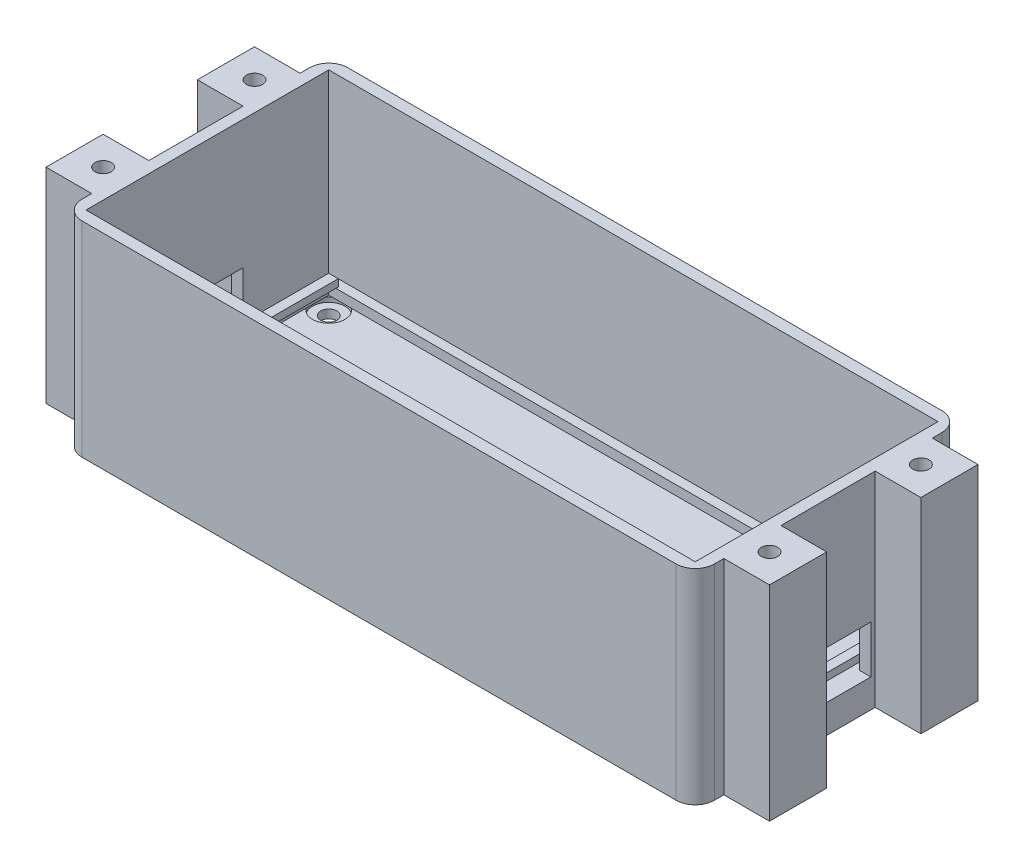
SolidWorks part; units mm, degrees
ref_plane "Front Plane" through (0, 0, 0) normal (0, 0, 1) x (1, 0, 0)
ref_plane "Top Plane" through (0, 0, 0) normal (0, 1, 0) x (1, 0, 0)
ref_plane "Right Plane" through (0, 0, 0) normal (1, 0, 0) x (0, 0, -1)
sketch "Sk_Shell" plane through (0, 0, 0) normal (0, 1, 0) x (1, 0, 0)
  line L0 (4, 0) -> (128.8, 0)
  line L1 (132.8, 4) -> (132.8, 51.8)
  line L2 (128.8, 55.8) -> (4, 55.8)
  line L3 (0, 51.8) -> (0, 4)
  arc A0 (128.8, 0) -> (132.8, 4) centre (128.8, 4) ccw
  arc A1 (132.8, 51.8) -> (128.8, 55.8) centre (128.8, 51.8) ccw
  arc A2 (4, 55.8) -> (0, 51.8) centre (4, 51.8) ccw
  arc A3 (0, 4) -> (4, 0) centre (4, 4) ccw
extrude "Shell" add sketch "Sk_Shell" along normal blind 43
sketch "Sk_Tabs" plane through (0, 0, 0) normal (0, 1, 0) x (1, 0, 0)
  line L1 (-9.6, 6) -> (0, 6)
  line L2 (-9.6, 6) -> (-9.6, 18)
  line L3 (-9.6, 18) -> (0, 18)
  line L4 (0, 6) -> (0, 18)
  line L6 (132.8, 6) -> (142.4, 6)
  line L7 (132.8, 6) -> (132.8, 18)
  line L8 (132.8, 18) -> (142.4, 18)
  line L9 (142.4, 6) -> (142.4, 18)
  line L11 (-9.6, 37.8) -> (0, 37.8)
  line L12 (-9.6, 37.8) -> (-9.6, 49.8)
  line L13 (-9.6, 49.8) -> (0, 49.8)
  line L14 (0, 37.8) -> (0, 49.8)
  line L16 (132.8, 37.8) -> (142.4, 37.8)
  line L17 (132.8, 37.8) -> (132.8, 49.8)
  line L18 (132.8, 49.8) -> (142.4, 49.8)
  line L19 (142.4, 37.8) -> (142.4, 49.8)
extrude "Mounting Tabs" add sketch "Sk_Tabs" along normal blind 43
ref_plane "Plane_FloorTop" through (0, 2.8, 0) normal (0, 1, 0) x (1, 0, 0)
sketch "Sk_Cavity" plane through (0, 2.8, 0) normal (0, 1, 0) x (1, 0, 0)
  line L1 (2.4, 2.4) -> (130.4, 2.4)
  line L2 (2.4, 2.4) -> (2.4, 53.4)
  line L3 (2.4, 53.4) -> (130.4, 53.4)
  line L4 (130.4, 2.4) -> (130.4, 53.4)
extrude "Cavity" cut sketch "Sk_Cavity" along normal through all
ref_plane "Plane_Lip" through (0, 4, 0) normal (0, 1, 0) x (1, 0, 0)
sketch "Sk_Lip" plane through (0, 4, 0) normal (0, 1, 0) x (1, 0, 0)
  line L1 (2.4, 2.4) -> (130.4, 2.4)
  line L2 (2.4, 2.4) -> (2.4, 53.4)
  line L3 (2.4, 53.4) -> (130.4, 53.4)
  line L4 (130.4, 2.4) -> (130.4, 53.4)
  line L6 (4.4, 4.4) -> (128.4, 4.4)
  line L7 (4.4, 4.4) -> (4.4, 51.4)
  line L8 (4.4, 51.4) -> (128.4, 51.4)
  line L9 (128.4, 4.4) -> (128.4, 51.4)
extrude "Board Lip" add sketch "Sk_Lip" along normal blind 2
ref_plane "Plane_LipTop" through (0, 6, 0) normal (0, 1, 0) x (1, 0, 0)
sketch "Sk_Rails" plane through (0, 6, 0) normal (0, 1, 0) x (1, 0, 0)
  line L1 (3.9, 3.9) -> (5.9, 3.9)
  line L2 (3.9, 3.9) -> (3.9, 51.9)
  line L3 (3.9, 51.9) -> (5.9, 51.9)
  line L4 (5.9, 3.9) -> (5.9, 51.9)
  line L6 (126.9, 3.9) -> (128.9, 3.9)
  line L7 (126.9, 3.9) -> (126.9, 51.9)
  line L8 (126.9, 51.9) -> (128.9, 51.9)
  line L9 (128.9, 3.9) -> (128.9, 51.9)
extrude "Board Rails" add sketch "Sk_Rails" along normal blind 1.5
sketch "Sk_SlotA" plane through (0, 0, 0) normal (1, 0, 0) x (0, 0, -1)
  line L1 (20.4, 6) -> (35.4, 6)
  line L2 (20.4, 6) -> (20.4, 16)
  line L3 (20.4, 16) -> (35.4, 16)
  line L4 (35.4, 6) -> (35.4, 16)
extrude "Cable Slot 15x10" cut sketch "Sk_SlotA" along normal blind 3
ref_plane "Plane_EndB" through (132.8, 0, 0) normal (1, 0, 0) x (0, 0, -1)
sketch "Sk_SlotB" plane through (132.8, 0, 0) normal (1, 0, 0) x (0, 0, -1)
  line L1 (18.9, 6) -> (36.9, 6)
  line L2 (18.9, 6) -> (18.9, 16)
  line L3 (18.9, 16) -> (36.9, 16)
  line L4 (36.9, 6) -> (36.9, 16)
extrude "Cable Slot 18x10" cut sketch "Sk_SlotB" against normal blind 3
sketch "Sk_TabHoles" plane through (0, 0, 0) normal (0, 1, 0) x (1, 0, 0)
  circle A0 centre (-3.6, 12) radius 1.7
  circle A1 centre (-3.6, 43.8) radius 1.7
  circle A2 centre (136.4, 12) radius 1.7
  circle A3 centre (136.4, 43.8) radius 1.7
extrude "Tab M3 Clearance Holes" cut sketch "Sk_TabHoles" against normal through all and the other way through all
sketch "Sk_FloorHoles" plane through (0, 0, 0) normal (0, 1, 0) x (1, 0, 0)
  circle A0 centre (5.9, 5.9) radius 1.7
  circle A1 centre (126.9, 5.9) radius 1.7
  circle A2 centre (5.9, 49.9) radius 1.7
  circle A3 centre (126.9, 49.9) radius 1.7
extrude "Floor M3 Clearance Holes" cut sketch "Sk_FloorHoles" along normal blind 2.8
sketch "Sk_CBore" plane through (0, 2.8, 0) normal (0, 1, 0) x (1, 0, 0)
  circle A0 centre (5.9, 5.9) radius 3.4
  circle A1 centre (126.9, 5.9) radius 3.4
  circle A2 centre (5.9, 49.9) radius 3.4
  circle A3 centre (126.9, 49.9) radius 3.4
extrude "Floor Counterbores" cut sketch "Sk_CBore" against normal blind 1
